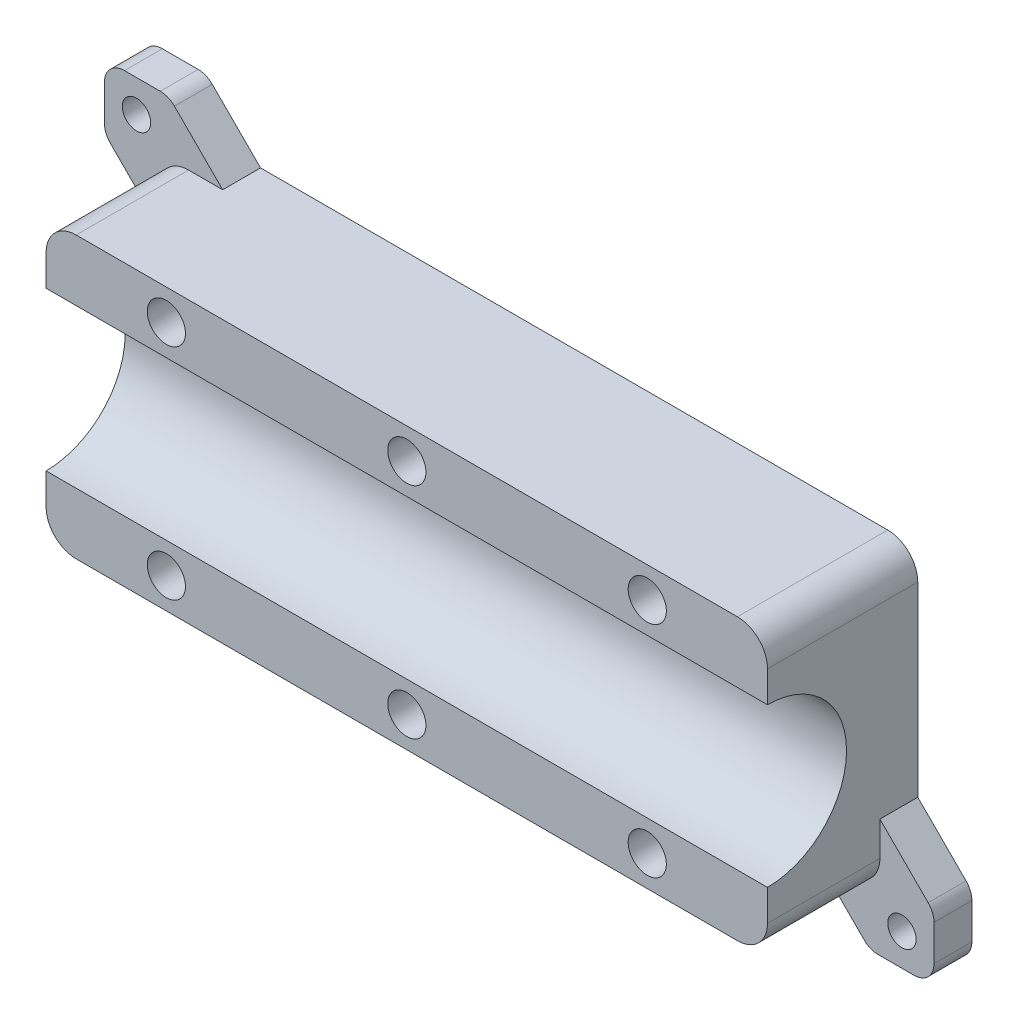
SolidWorks part; units mm, degrees
material "Custom Plastic"
ref_plane "X-Y Datum" through (0, 0, 0) normal (0, 0, 1) x (1, 0, 0)
ref_plane "X-Z Datum" through (0, 0, 0) normal (0, 1, 0) x (1, 0, 0)
ref_plane "Y-Z Datum" through (0, 0, 0) normal (1, 0, 0) x (0, 0, -1)
sketch "Sketch1" plane through (0, 0, 0) normal (0, 0, 1) x (1, 0, 0)
  line L1 (-57.15, 22.225) -> (57.15, 22.225)
  line L2 (-57.15, 22.225) -> (-57.15, -22.225)
  line L3 (-57.15, -22.225) -> (57.15, -22.225)
  line L4 (57.15, 22.225) -> (57.15, -22.225)
  line L5 (-57.15, 22.225) -> (57.15, -22.225) construction
  line L6 (-57.15, -22.225) -> (57.15, 22.225) construction
  point P0 (0, 0)
  dimension "D1" = 114.3
  dimension "D2" = 44.45
extrude "Boss-Extrude1" add sketch "Sketch1" along normal blind 5
sketch "Sketch2" plane through (-57.15, 0, 0) normal (-1, 0, 0) x (0, 0, 1)
  line L0 (5, -22.225) -> (0, -22.225) construction
  line L1 (5, 22.225) -> (23.8125, 22.225)
  line L2 (5, 22.225) -> (5, -22.225)
  line L3 (5, -22.225) -> (23.8125, -22.225)
  line L4 (23.8125, 22.225) -> (23.8125, -22.225)
  circle A0 centre (23.8125, 0) radius 12.0269 construction
  circle A1 centre (23.8125, 0) radius 12.0269 construction
  circle A2 centre (23.8125, 0) radius 12.5269
  line M9 (5, -22.225) -> (5, 22.225)
  dimension "D1" = 0.5
extrude "Boss-Extrude2" add sketch "Sketch2" against normal blind 114.3 contours A2 L4 L1 L3 M9
sketch "Sketch3" plane through (0, 0, 23.8125) normal (0, 0, 1) x (1, 0, 0)
  line L0 (-57.15, 17.3759) -> (57.15, 17.3759) construction
  line L1 (-57.15, 22.225) -> (-57.15, 12.5269) construction
  line L2 (57.15, 22.225) -> (57.15, 12.5269) construction
  circle A0 centre (0, 17.3759) radius 3.025
  dimension "D1" = 6.05
extrude "Cut-Extrude1" cut sketch "Sketch3" against normal blind 5.5
pattern_linear "LPattern1" count 2 spacing 38.1 along (1, 0, 0) count 2 spacing 38.1 along (-1, 0, 0) of "Cut-Extrude1"
mirror "Mirror1" about plane through (0, 0, 0) normal (0, 1, 0) of "LPattern1", "Cut-Extrude1"
sketch "Sketch4" plane through (0, 0, 0) normal (0, 0, 1) x (1, 0, 0)
  line L0 (55.5625, -20.6375) -> (65.7225, -30.7975) construction
  line L5 (-65.7225, 20.6375) -> (-55.5625, 20.6375)
  line L6 (-65.7225, 20.6375) -> (-65.7225, 30.7975)
  line L7 (-65.7225, 30.7975) -> (-55.5625, 30.7975)
  line L8 (-55.5625, 20.6375) -> (-55.5625, 30.7975)
  line L9 (55.5625, -30.7975) -> (65.7225, -30.7975)
  line L10 (55.5625, -30.7975) -> (55.5625, -20.6375)
  line L11 (55.5625, -20.6375) -> (65.7225, -20.6375)
  line L12 (65.7225, -30.7975) -> (65.7225, -20.6375)
  line L13 (-65.7225, 30.7975) -> (-55.5625, 20.6375)
  line L14 (57.15, 22.225) -> (-57.15, 22.225) construction
  line L15 (-57.15, 22.225) -> (-57.15, 12.5269) construction
  line L16 (57.15, -12.5269) -> (57.15, -22.225) construction
  line L17 (57.15, -22.225) -> (-57.15, -22.225) construction
  line L18 (-55.5625, 30.7975) -> (-46.99, 22.225)
  line L19 (-65.7225, 20.6375) -> (-55.5625, 30.7975)
  line L20 (-65.7225, 20.6375) -> (-57.15, 12.065)
  line L21 (55.5625, -30.7975) -> (46.99, -22.225)
  line L22 (65.7225, -20.6375) -> (55.5625, -30.7975) construction
  line L23 (65.7225, -20.6375) -> (57.15, -12.065)
  line L24 (57.15, -10.7701) -> (57.15, -22.225)
  line L25 (57.15, -22.225) -> (-57.15, -22.225)
  line L26 (-57.15, 22.225) -> (-57.15, 10.3851)
  line L27 (57.15, 22.225) -> (-57.15, 22.225)
  line L28 (-57.15, 12.5269) -> (-57.15, -12.5269) construction
  line L29 (57.15, -12.5269) -> (57.15, 12.5269) construction
  circle A0 centre (60.6425, -25.7175) radius 2 construction
  circle A1 centre (-60.6425, 25.7175) radius 2 construction
  dimension "D1" = 4
  dimension "D2" = 4
  dimension "D3" = 10.16
  dimension "D4" = 10.16
  dimension "D5" = 10.16
  dimension "D6" = 10.16
  dimension "D7" = 1.5875
  dimension "D8" = 1.5875
  dimension "D9" = 1.5875
  dimension "D10" = 1.5875
extrude "Boss-Extrude3" add sketch "Sketch4" along normal blind 6 contours L13 L6 L5 | L7 L13 L8 | L9 L12 L11 L10 | L27 L8 L19 L13 | L27 L18 L8 | L26 L13 L19 L5 | L26 L5 L20 | L23 L24 L11 | L10 L25 L21
hole_wizard "M4 Clearance Hole1" positions "Sketch5" profile "Sketch6" hole size "M4" standard "ANSI Metric" end condition through all
sketch "Sketch5" plane through (0, 0, 6) normal (0, 0, 1) x (1, 0, 0)
  point P2 (-60.6425, 25.7175)
  point P5 (60.6425, -25.7175)
sketch "Sketch6" plane through (-60.6425, 25.7175, 6) normal (1, 0, 0) x (0, -1, 0)
  line L0 (0, 0) -> (0, 6)
  line L1 (0, 6) -> (2.25, 6)
  line L2 (2.25, 6) -> (2.25, 0)
  line L5 (2.25, 0) -> (0, 0)
  line L11 (0, -6.35) -> (0, 107.95) construction
  dimension "Thru Hole Dia." = 4.5
  dimension "Thru Hole Depth" = 6
fillet "Fillet3" radius 3.175 6 edges at (-55.5625, 30.7975, 3) (-65.7225, 30.7975, 3) (-65.7225, 20.6375, 3) (65.7225, -20.6375, 3) (65.7225, -30.7975, 3) (55.5625, -30.7975, 3)
fillet "Fillet4" radius 4.7625 4 edges at (57.15, 22.225, 11.9062) (-57.15, 22.225, 14.9062) (57.15, -22.225, 14.9062) (-57.15, -22.225, 11.9062)
